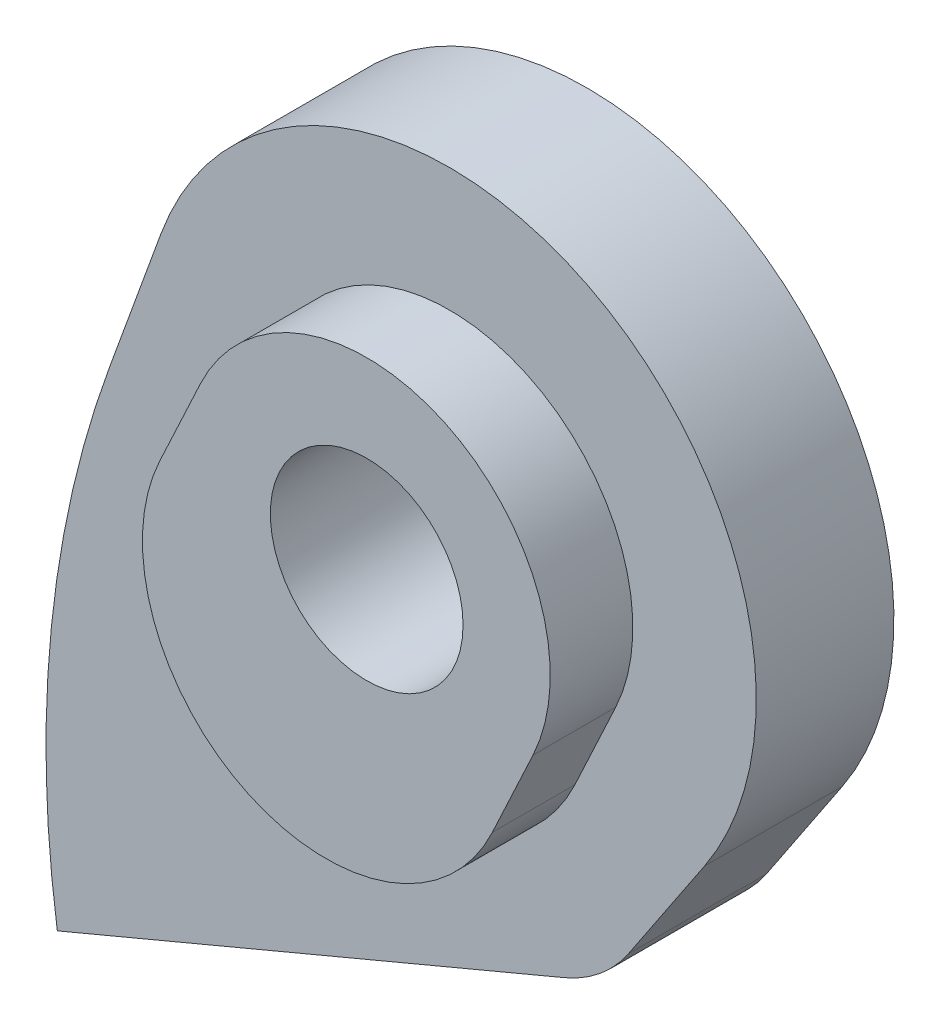
SolidWorks part; units mm, degrees
ref_plane "Front Plane" through (0, 0, 0) normal (0, 0, 1) x (1, 0, 0)
ref_plane "Top Plane" through (0, 0, 0) normal (0, 1, 0) x (1, 0, 0)
ref_plane "Right Plane" through (0, 0, 0) normal (1, 0, 0) x (0, 0, -1)
sketch "Sketch6" plane through (0, 0, 0) normal (0, 0, 1) x (1, 0, 0)
  line L0 (0, 0) -> (40.1809, 0) construction
  line L1 (0, 0) -> (35.507, 92.499) construction
  line L2 (19.3519, 50.4133) -> (0.4719, 63.0164) construction
  line L3 (19.3519, 50.4133) -> (-36.1025, 71.7003) construction
  dimension "D1" = 69
  dimension "D2" = 54
  dimension "D3" = 22.7
  dimension "D4" = 5
sketch "Sketch3" plane through (0, 0, 0) normal (0, 0, 1) x (1, 0, 0)
  line L0 (24.1743, 72.523) -> (120.8717, 72.523) construction
  line L6 (11.8164, 60.2529) -> (11.7284, 60.3116)
  line L7 (7.3748, 53.5992) -> (5.9136, 54.5745)
  line L8 (19.3519, 50.4133) -> (0.4719, 63.0164) construction
  line L9 (-6.1719, 82.4206) -> (-7.2903, 79.3479)
  line L10 (19.3519, 50.4133) -> (13.2479, 41.2693) construction
  line L11 (19.3519, 50.4133) -> (31.6629, 68.8558) construction
  line L12 (4.0204, 73.9337) -> (5.6789, 76.4182)
  line L14 (0.1147, 80.1325) -> (27.1455, 62.0885) construction
  line L15 (0.1147, 80.1325) -> (-7.2903, 79.3479) construction
  line L16 (0.1147, 80.1325) -> (0.1147, 91.1913) construction
  line L17 (0.1147, 80.1325) -> (-6.1719, 82.4206) construction
  arc A0 (13.4996, 47.0498) -> (20.2139, 57.1081) centre (19.3519, 50.4133) ccw
  arc A1 (20.2139, 57.1081) -> (11.8164, 60.2529) centre (22.7223, 76.5904) cw
  arc A2 (13.4996, 47.0498) -> (7.3748, 53.5992) centre (-3.5311, 37.2616) ccw
  arc A3 (11.7284, 60.3116) -> (6.8662, 65.9311) centre (19.4923, 71.9424) cw
  arc A4 (-6.1719, 82.4206) -> (5.6789, 76.4182) centre (0.1147, 80.1325) cw
  arc A5 (6.8662, 65.9311) -> (4.9012, 68.3908) centre (0.6246, 62.9595) ccw
  arc A6 (4.9012, 68.3908) -> (4.0204, 73.9337) centre (7.4585, 71.6386) cw
  arc A7 (5.9136, 54.5745) -> (0.4148, 56.2666) centre (0.3298, 46.2096) ccw
  arc A10 (0.4148, 56.2666) -> (-5.2798, 59.4837) centre (0.4719, 63.0164) cw
  circle A12 centre (19.3519, 50.4133) radius 2.75
  circle A13 centre (0.4719, 63.0164) radius 2.75
  circle A17 centre (0.1147, 80.1325) radius 2.1
  arc A18 (-7.2903, 79.3479) -> (-5.2798, 59.4837) centre (14.2795, 71.4971) ccw
  dimension "D1" = 5.5
  dimension "D2" = 5.5
  dimension "D3" = 4
  dimension "D5" = 4
  dimension "D6" = 4
  dimension "D4" = 4.2
  dimension "D17" = 70
  dimension "D18" = 3.27
  dimension "D14" = 6.69
  dimension "D7" = 3
  dimension "D8" = 4
  dimension "D9" = 3
  dimension "D10" = 4
  dimension "D11" = 19
  dimension "D12" = 19
  dimension "D13" = 22
  dimension "D15" = 32.5
  dimension "D16" = 14
extrude "Boss-Extrude2" add sketch "Sketch3" along normal blind 11
sketch "Sketch13" plane through (0, 0, 0) normal (0, 0, -1) x (-1, 0, 0)
  line L0 (-5.6789, 76.4182) -> (-4.0204, 73.9337)
  line L1 (-2.6258, 72.7829) -> (8.4277, 68.1397)
  line L2 (6.1719, 82.4206) -> (7.2903, 79.3479)
  arc A0 (-5.6789, 76.4182) -> (6.1719, 82.4206) centre (-0.1147, 80.1325) cw
  arc A1 (6.1719, 82.4206) -> (-5.6789, 76.4182) centre (-0.1147, 80.1325) ccw construction
  arc A2 (-4.0204, 73.9337) -> (-2.6258, 72.7829) centre (-1.4106, 75.6758) ccw
  arc A3 (5.2798, 59.4837) -> (7.2903, 79.3479) centre (-14.2795, 71.4971) ccw construction
  arc A4 (8.4277, 68.1397) -> (7.2903, 79.3479) centre (-14.2795, 71.4971) ccw
extrude "Boss-Extrude4" add sketch "Sketch13" along normal blind 3
sketch "Sketch12" plane through (0, 0, -3) normal (0, 0, -1) x (-1, 0, 0)
  line L0 (8.0136, 76.9658) -> (4.9242, 69.6114)
  line L4 (4.9242, 69.6114) -> (8.4277, 68.1397)
  line L5 (-2.6258, 72.7829) -> (8.4277, 68.1397) construction
  line L8 (-2.6258, 72.7829) -> (8.4277, 68.1397) construction
  arc A0 (8.0136, 76.9658) -> (8.4277, 68.1397) centre (-14.2795, 71.4971) cw
  arc A1 (5.2798, 59.4837) -> (8.4277, 68.1397) centre (-14.2795, 71.4971) ccw construction
  dimension "D1" = 3.8
  dimension "D2" = 90
extrude "Boss-Extrude3" add sketch "Sketch12" along normal blind 3
sketch "Sketch14" plane through (0, 0, 0) normal (0, 1, 0) x (1, 0, 0)
  line L0 (19.3519, 0) -> (-36.1025, 0) construction
  line L1 (-15.2308, 0) -> (32.0549, 0)
  line L2 (-15.2308, 0) -> (-15.2308, -12.5955)
  line L3 (-15.2308, -12.5955) -> (32.0549, -12.5955)
  line L4 (32.0549, 0) -> (32.0549, -12.5955)
extrude "Cut-Extrude1" cut sketch "Sketch14" along normal through all
sketch "Sketch16" plane through (0, 0, 0) normal (0, 0, 1) x (1, 0, 0)
  line L0 (0.1147, 80.1325) -> (-0.7728, 78.2293) construction
  line L1 (3.7399, 78.4421) -> (2.8524, 76.5388)
  line L2 (-3.5105, 81.823) -> (-4.398, 79.9198)
  line L3 (0.1147, 80.1325) -> (0.1147, 75.6752) construction
  arc A0 (3.7399, 78.4421) -> (-3.5105, 81.823) centre (0.1147, 80.1325) ccw
  arc A1 (-4.398, 79.9198) -> (2.8524, 76.5388) centre (-0.7728, 78.2293) ccw
  point P3 (-0.3291, 79.1809)
  dimension "D1" = 4
  dimension "D2" = 25
  dimension "D3" = 2.1
extrude "Boss-Extrude5" add sketch "Sketch16" along normal blind 1.8
sketch "Sketch15" plane through (0, 0, 1.8) normal (0, 0, 1) x (1, 0, 0)
  circle A0 centre (0.1147, 80.1325) radius 2.1
  dimension "D1" = 4.2
extrude "Cut-Extrude2" cut sketch "Sketch15" against normal through all
